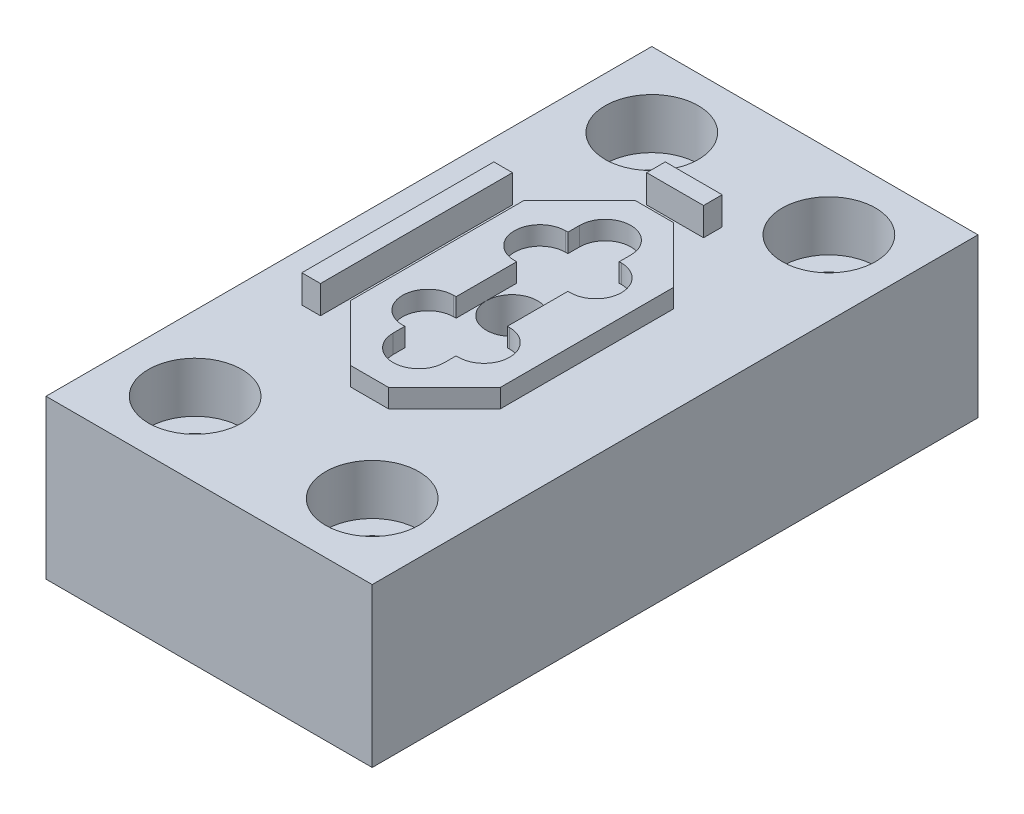
SolidWorks part; units mm, degrees
ref_plane "Ebene vorne" through (0, 0, 0) normal (0, 0, 1) x (1, 0, 0)
ref_plane "Ebene oben" through (0, 0, 0) normal (0, 1, 0) x (1, 0, 0)
ref_plane "Ebene rechts" through (0, 0, 0) normal (1, 0, 0) x (0, 0, -1)
sketch "Skizze1" plane through (0, 0, 0) normal (0, 1, 0) x (1, 0, 0)
  line L0 (-17.5, 0) -> (17.5, 0) construction
  line L1 (-17.5, 32.5) -> (17.5, 32.5)
  line L2 (-17.5, 32.5) -> (-17.5, -32.5)
  line L3 (-17.5, -32.5) -> (17.5, -32.5)
  line L4 (17.5, 32.5) -> (17.5, -32.5)
  line L5 (0, 32.5) -> (0, -32.5) construction
  point P8 (0, 0)
  dimension "D1" = 65
  dimension "D2" = 35
extrude "Aufsatz-Linear austragen1" add sketch "Skizze1" along normal blind 20
sketch "Skizze4" plane through (0, 20, 0) normal (0, 1, 0) x (1, 0, 0)
  line L1 (-10.25, 17.5) -> (10.25, 17.5)
  line L2 (-10.25, 17.5) -> (-10.25, -17.5)
  line L3 (-10.25, -17.5) -> (10.25, -17.5)
  line L4 (10.25, 17.5) -> (10.25, -17.5)
  line L5 (-10.25, 17.5) -> (10.25, -17.5) construction
  line L6 (-10.25, -17.5) -> (10.25, 17.5) construction
  point P0 (0, 0)
  dimension "D1" = 35
  dimension "D2" = 20.5
extrude "Schnitt-Linear austragen3" cut sketch "Skizze4" against normal blind 1
sketch "Skizze6" plane through (0, 20, 0) normal (0, 1, 0) x (1, 0, 0)
  line L12 (17.5, 32.5) -> (-17.5, 32.5) construction
  line L17 (10.25, 32.5) -> (8.05, 32.5)
  line L22 (10.25, 32.5) -> (10.25, -32.5)
  line L23 (10.25, -32.5) -> (8.05, -32.5)
  line L24 (8.05, 32.5) -> (8.05, -32.5)
  line L25 (-17.5, -32.5) -> (17.5, -32.5) construction
  line L26 (-10.25, 17.5) -> (-10.25, -17.5) construction
  line L27 (-10.25, 32.5) -> (-8.05, 32.5)
  line L28 (-10.25, 32.5) -> (-10.25, -32.5)
  line L29 (-10.25, -32.5) -> (-8.05, -32.5)
  line L30 (-8.05, 32.5) -> (-8.05, -32.5)
  line L31 (10.25, -17.5) -> (10.25, 17.5) construction
  dimension "D3" = 2.2
  dimension "D4" = 2.2
sketch "Skizze7" plane through (0, 20, 0) normal (0, 1, 0) x (1, 0, 0)
  line L0 (17.5, -32.5) -> (17.5, 32.5) construction
  line L1 (17.5, 17.5) -> (-17.5, 17.5)
  line L2 (17.5, 17.5) -> (17.5, 15.3)
  line L3 (17.5, 15.3) -> (-17.5, 15.3)
  line L4 (-17.5, 17.5) -> (-17.5, 15.3)
  line L5 (-17.5, 32.5) -> (-17.5, -32.5) construction
  line L6 (-10.25, -17.5) -> (10.25, -17.5) construction
  line L7 (17.5, -17.5) -> (-17.5, -17.5)
  line L8 (17.5, -17.5) -> (17.5, -15.3)
  line L9 (17.5, -15.3) -> (-17.5, -15.3)
  line L10 (-17.5, -17.5) -> (-17.5, -15.3)
  line L11 (10.25, 17.5) -> (-10.25, 17.5) construction
  dimension "D1" = 2.2
  dimension "D2" = 2.2
extrude "Schnitt-Linear austragen4" cut sketch "Skizze6" against normal blind 3
extrude "Schnitt-Linear austragen5" cut sketch "Skizze7" against normal blind 3
sketch "Skizze8" plane through (0, 20, 0) normal (0, 1, 0) x (1, 0, 0)
  line L0 (-10.25, -15.3) -> (-17.5, -15.3) construction
  line L1 (10.25, 17.5) -> (17.5, 17.5)
  line L2 (10.25, 17.5) -> (10.25, 32.5)
  line L3 (10.25, 32.5) -> (17.5, 32.5)
  line L4 (17.5, 17.5) -> (17.5, 32.5)
  line L5 (10.25, -17.5) -> (17.5, -17.5)
  line L6 (10.25, -17.5) -> (10.25, -32.5)
  line L7 (10.25, -32.5) -> (17.5, -32.5)
  line L8 (17.5, -17.5) -> (17.5, -32.5)
  line L9 (-10.25, -17.5) -> (-17.5, -17.5)
  line L10 (-10.25, -17.5) -> (-10.25, -32.5)
  line L11 (-10.25, -32.5) -> (-17.5, -32.5)
  line L12 (-17.5, -17.5) -> (-17.5, -32.5)
  line L13 (-10.25, 17.5) -> (-17.5, 17.5)
  line L14 (-10.25, 17.5) -> (-10.25, 32.5)
  line L15 (-10.25, 32.5) -> (-17.5, 32.5)
  line L16 (-17.5, 17.5) -> (-17.5, 32.5)
  line L17 (-17.5, 15.3) -> (-12.25, 15.3)
  line L18 (-17.5, 15.3) -> (-17.5, -15.3)
  line L19 (-17.5, -15.3) -> (-12.25, -15.3)
  line L20 (-12.25, 15.3) -> (-12.25, -15.3)
  line L21 (8.05, -17.5) -> (8.05, -32.5) construction
  line L22 (-8.05, -32.5) -> (8.05, -32.5)
  line L23 (-8.05, -32.5) -> (-8.05, -17.5)
  line L24 (-8.05, -17.5) -> (8.05, -17.5)
  line L25 (8.05, -32.5) -> (8.05, -17.5)
  line L26 (10.25, 15.3) -> (17.5, 15.3) construction
  line L27 (17.5, -15.3) -> (10.25, -15.3)
  line L28 (17.5, -15.3) -> (17.5, 15.3)
  line L29 (17.5, 15.3) -> (10.25, 15.3)
  line L30 (10.25, -15.3) -> (10.25, 15.3)
  line L31 (-8.05, 17.5) -> (-8.05, 32.5) construction
  line L32 (8.05, 32.5) -> (-8.05, 32.5)
  line L33 (8.05, 32.5) -> (8.05, 19.5)
  line L34 (8.05, 19.5) -> (-8.05, 19.5)
  line L35 (-8.05, 32.5) -> (-8.05, 19.5)
  line L36 (8.05, 17.5) -> (-8.05, 17.5) construction
  line L37 (10.25, -15.3) -> (10.25, 15.3) construction
  line L38 (-8.05, -17.5) -> (8.05, -17.5) construction
  line L39 (-10.25, 15.3) -> (-10.25, -15.3) construction
  dimension "D1" = 2
  dimension "D2" = 0
  dimension "D3" = 0
  dimension "D4" = 2
extrude "Schnitt-Linear austragen6" cut sketch "Skizze8" against normal blind 3
sketch "Skizze17" plane through (0, 20, 0) normal (0, 1, 0) x (1, 0, 0)
  line L0 (-10.25, 15.3) -> (-10.25, -15.3) construction
  line L1 (-12.25, -15.3) -> (-10.25, -15.3)
  line L2 (-12.25, -15.3) -> (-12.25, -10.3)
  line L3 (-12.25, -10.3) -> (-10.25, -10.3)
  line L4 (-10.25, -15.3) -> (-10.25, -10.3)
  line L5 (-10.25, 15.3) -> (-10.25, -15.3) construction
  line L6 (-12.25, 15.3) -> (-10.25, 15.3)
  line L7 (-12.25, 15.3) -> (-12.25, 10.3)
  line L8 (-12.25, 10.3) -> (-10.25, 10.3)
  line L9 (-10.25, 15.3) -> (-10.25, 10.3)
  line L10 (-8.05, 19.5) -> (8.05, 19.5) construction
  line L11 (-8.05, 17.5) -> (-3.05, 17.5)
  line L12 (-8.05, 17.5) -> (-8.05, 19.5)
  line L13 (-8.05, 19.5) -> (-3.05, 19.5)
  line L14 (-3.05, 17.5) -> (-3.05, 19.5)
  line L16 (8.05, 17.5) -> (3.05, 17.5)
  line L17 (8.05, 17.5) -> (8.05, 19.5)
  line L18 (8.05, 19.5) -> (3.05, 19.5)
  line L19 (3.05, 17.5) -> (3.05, 19.5)
  dimension "D1" = 5
  dimension "D2" = 5
  dimension "D3" = 5
  dimension "D4" = 5
sketch "Skizze9" plane through (0, 19, 0) normal (0, 1, 0) x (1, 0, 0)
  line L0 (0, 10) -> (0, -10) construction
  line L1 (2.75, 10) -> (2.75, -10)
  line L2 (-2.75, 10) -> (-2.75, -10)
  line L3 (3, 6) -> (-3, 6) construction
  line L4 (3, 3.25) -> (-3, 3.25)
  line L5 (3, 8.75) -> (-3, 8.75)
  line L6 (3, -6) -> (-3, -6) construction
  line L7 (3, -8.75) -> (-3, -8.75)
  line L8 (3, -3.25) -> (-3, -3.25)
  arc A0 (2.75, 10) -> (-2.75, 10) centre (0, 10) ccw
  arc A1 (-2.75, -10) -> (2.75, -10) centre (0, -10) ccw
  arc A2 (3, 3.25) -> (3, 8.75) centre (3, 6) ccw
  arc A3 (-3, 8.75) -> (-3, 3.25) centre (-3, 6) ccw
  arc A4 (3, -8.75) -> (3, -3.25) centre (3, -6) ccw
  arc A5 (-3, -3.25) -> (-3, -8.75) centre (-3, -6) ccw
  point P2 (0, 0)
  point P10 (0, 6)
  point P16 (0, -6)
  dimension "D1" = 5.5
  dimension "D2" = 6
  dimension "D3" = 6
  dimension "D4" = 5.5
  dimension "D5" = 5.5
  dimension "D6" = 20
  dimension "D7" = 6
  dimension "D8" = 6
extrude "Schnitt-Linear austragen7" cut sketch "Skizze9" against normal blind 2 contours L1 L5 L2 L4 | L8 L1 L4 L2 | L1 L8 L2 L7 | L2 A1 L1 L7 | L7 A4 L8 L1 | L8 A5 L7 L2 | L5 A3 L4 L2 | L4 A2 L5 L1 | L1 A0 L2 L5
sketch "Skizze10" plane through (0, 20, 0) normal (0, 1, 0) x (1, 0, 0)
  circle A0 centre (0, 0) radius 2.75
  dimension "D1" = 5.5
extrude "Schnitt-Linear austragen8" cut sketch "Skizze10" against normal blind 14
hole_wizard "Kernloch für M5 Gewinde1" positions "Skizze11" profile "Skizze12" hole size "M5" standard "DIN"
sketch "Skizze11" plane through (0, 0, -32.5) normal (0, 0, -1) x (-1, 0, 0)
  line L0 (-17.5, 17) -> (17.5, 17) construction
  line L1 (-17.5, 17) -> (-17.5, 0) construction
  point P0 (0, 7)
  dimension "D1" = 10
  dimension "D2" = 17.5
sketch "Skizze12" plane through (0, 7, -32.5) normal (1, 0, 0) x (0, 1, 0)
  line L0 (0, 0) -> (0, 36.2618)
  line L1 (0, 36.2618) -> (2.1, 35)
  line L2 (2.1, 35) -> (2.1, 0)
  line L5 (2.1, 0) -> (0, 0)
  line L10 (0, 36.2618) -> (-2.1, 35) construction
  line L11 (0, -6.35) -> (0, 107.95) construction
  dimension "Bohrerdurchmesser" = 4.2
  dimension "Bohrungstiefe" = 35
  dimension "Spitzenwinkel" = 118
extrude "Schnitt-Linear austragen11" cut sketch "Skizze17" against normal blind 3
chamfer "Fase1" distance 6 4 edges at (8.05, 18, 15.3) (-8.05, 18, 15.3) (-8.05, 18, -15.3) (8.05, 18, -15.3)
hole_wizard "Stirnsenkung für M5 Zylinderschraube mit Innensechskant1" positions "Skizze21" profile "Skizze22" counterbore size "M5" standard "DIN" end condition through all
sketch "Skizze21" plane through (78.1259, 17, -61.7446) normal (0, 1, 0) x (1, 0, 0)
  point P0 (-68.6259, -37.2446)
  point P1 (-87.6259, -37.2446)
  point P2 (-87.6259, -86.2446)
  point P3 (-68.6259, -86.2446)
sketch "Skizze22" plane through (9.5, 17, -24.5) normal (1, 0, 0) x (0, 0, 1)
  line L0 (0, 0) -> (0, 17)
  line L1 (0, 17) -> (2.75, 17)
  line L3 (2.75, 17) -> (2.75, 5.4)
  line L4 (2.75, 5.4) -> (5, 5.4)
  line L5 (5, 5.4) -> (5, 0)
  line L7 (5, 0) -> (0, 0)
  line L11 (0, -6.35) -> (0, 107.95) construction
  dimension "Bohrerdurchmesser" = 5.5
  dimension "Bohrungstiefe" = 17
  dimension "Senkdurchmesser2" = 10
  dimension "Senktiefe2" = 5.4
